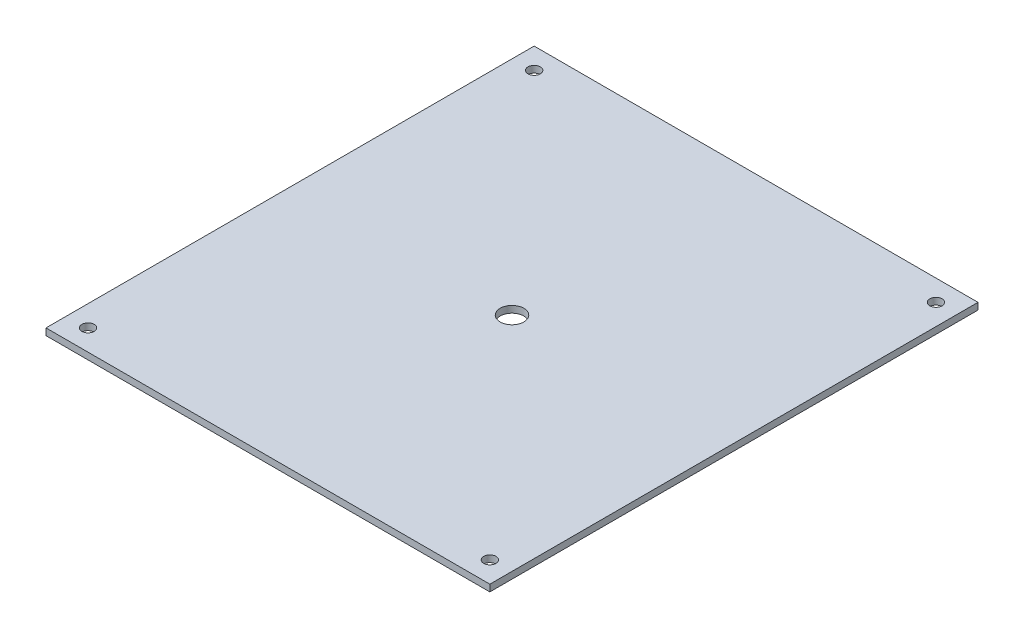
SolidWorks part; units mm, degrees
ref_plane "Front Plane" through (0, 0, 0) normal (0, 0, 1) x (1, 0, 0)
ref_plane "Top Plane" through (0, 0, 0) normal (0, 1, 0) x (1, 0, 0)
ref_plane "Right Plane" through (0, 0, 0) normal (1, 0, 0) x (0, 0, -1)
sketch "Sketch1" plane through (0, 0, 0) normal (0, 1, 0) x (1, 0, 0)
  line L1 (70.15, -77.15) -> (-70.15, -77.15)
  line L2 (70.15, -77.15) -> (70.15, 77.15)
  line L3 (70.15, 77.15) -> (-70.15, 77.15)
  line L4 (-70.15, -77.15) -> (-70.15, 77.15)
  line L5 (70.15, -77.15) -> (-70.15, 77.15) construction
  line L6 (70.15, 77.15) -> (-70.15, -77.15) construction
  point P0 (0, 0)
  dimension "D1" = 140.3
  dimension "D2" = 154.3
extrude "Boss-Extrude1" add sketch "Sketch1" along normal blind 2.13
sketch "Sketch2" plane through (0, 0, 0) normal (0, 1, 0) x (1, 0, 0)
  line L1 (63.5, 70.5) -> (-63.5, 70.5) construction
  line L2 (63.5, 70.5) -> (63.5, -70.5) construction
  line L3 (63.5, -70.5) -> (-63.5, -70.5) construction
  line L4 (-63.5, 70.5) -> (-63.5, -70.5) construction
  line L5 (63.5, 70.5) -> (-63.5, -70.5) construction
  line L6 (63.5, -70.5) -> (-63.5, 70.5) construction
  circle A0 centre (-63.5, -70.5) radius 1.94
  circle A1 centre (63.5, -70.5) radius 1.94
  circle A2 centre (-63.5, 70.5) radius 1.94
  circle A3 centre (63.5, 70.5) radius 1.94
  point P4 (0, 0)
  dimension "D3" = 3.88
  dimension "D4" = 3.88
  dimension "D5" = 3.88
  dimension "D6" = 3.88
  dimension "D1" = 127
  dimension "D2" = 141
extrude "Cut-Extrude1" cut sketch "Sketch2" along normal blind 31.13
sketch "Sketch3" plane through (0, 0, 0) normal (0, 1, 0) x (1, 0, 0)
  circle A0 centre (0, 0) radius 3.75
extrude "Cut-Extrude2" cut sketch "Sketch3" along normal blind 20
